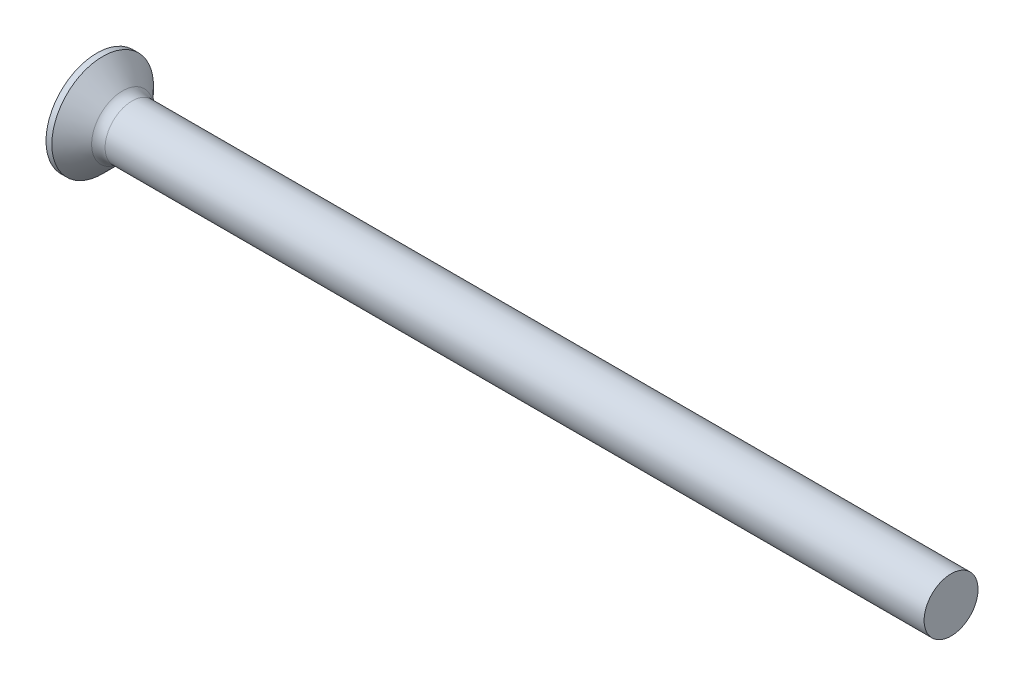
SolidWorks part; units mm, degrees
revolve "Base-Revolve" add sketch "BodySke" angle 360 about L5
sketch "BodySke" plane through (0, 0, 0) normal (0, 0, 1) x (1, 0, 0)
  line L0 (0, 0) -> (0, 5.65)
  line L1 (0, 5.65) -> (0.65, 5.65)
  line L2 (3.3, 3) -> (95, 3)
  line L3 (95, 3) -> (95, 0)
  line L4 (95, 0) -> (0, 0)
  line L5 (-6.35, 0) -> (82.55, 0) construction
  line L6 (3.3, -3) -> (95, -3) construction
  line L7 (0.65, -5.65) -> (3.3, -3) construction
  line L8 (0.65, 5.65) -> (3.3, 3)
  line L9 (0, -5.65) -> (0.65, -5.65) construction
  line L10 (4.3, 4.5875) -> (4.3, -4.9375) construction
  line L11 (57, 6.35) -> (57, -3.175) construction
  dimension "Diameter" = 6
  dimension "Length" = 95
  dimension "Head_ht" = 3.3
  dimension "Head_dia" = 11.3
  dimension "Head_ang" = 90
  dimension "D6" = 0.65
  dimension "Advance" = 1
  dimension "Thread_nom" = 38
cosmetic thread "ThreadCosmetic" [suppressed] parameters "Thread_length"=38, "Thread_minor"=4.891
ref_plane "Plane1" through (0, 0, 0) normal (0, 0, 1) x (1, 0, 0)
ref_plane "Plane2" through (0, 0, 0) normal (0, 1, 0) x (1, 0, 0)
ref_plane "Plane3" through (0, 0, 0) normal (1, 0, 0) x (0, 0, -1)
other "Configuration Table"
fillet "Fillet1" radius 1.5 1 edges at (3.3, 0, 3)
sketch "Sketch3" plane through (0, 0, 0) normal (-1, 0, 0) x (0, 0, 1)
  line L0 (-0.71, 3.3) -> (0.71, 3.3)
  line L1 (0.71, 3.3) -> (0.71, -3.3)
  line L2 (0.71, -3.3) -> (-0.71, -3.3)
  line L3 (-0.71, -3.3) -> (-0.71, 3.3)
  dimension "Cross_dia" = 6.6
  dimension "Cross_width" = 1.42
  dimension "D1" = 3.3
  dimension "D2" = 0.71
ref_plane "Plane4" through (3.45, 0, 0) normal (-1, 0, 0) x (0, 0, 1)
sketch "Sketch4" plane through (3.45, 0, 0) normal (-1, 0, 0) x (0, 0, 1)
  line L0 (-0.71, 1.5799) -> (0.71, 1.5799)
  line L3 (0.71, 1.5799) -> (0.71, -1.5799)
  line L4 (0.71, -1.5799) -> (-0.71, -1.5799)
  line L5 (-0.71, -1.5799) -> (-0.71, 1.5799)
  dimension "D2" = 3.1598
  dimension "D1" = 1.42
  dimension "D4" = 1.5799
  dimension "D3" = 0.71
loft "Recess" cut profiles "Sketch3", "Sketch4"
pattern_circular "RecPat" count 2 every 90 about axis through (0, 0, 0) along (1, 0, 0) of "Recess"
sketch "RecCorSke" plane through (0, 0, 0) normal (0, 0, 1) x (1, 0, 0)
  line L0 (-3.175, 0) -> (15.875, 0) construction
  line L2 (0, 0) -> (0, 1.5217)
  line L3 (0, 1.5217) -> (3.45, 1.2805)
  line L4 (3.45, 1.2805) -> (3.8661, 0)
  line L5 (3.8661, 0) -> (0, 0)
  dimension "Diameter" = 2.561
  dimension "Depth" = 3.45
  dimension "Draft_angle" = 4
  dimension "Bottom_angle" = 18
revolve "RecessCore" cut sketch "RecCorSke" angle 360 about L0
sketch "ThdSchSke" plane through (0, 0, 0) normal (0, 0, 1) x (1, 0, 0)
  line L0 (57, -2.4455) -> (56.6117, -3)
  line L1 (57, -2.4455) -> (57.3883, -3)
  line L2 (57.3883, -3) -> (57.3883, -3.75)
  line L3 (-3.175, 0) -> (5.1513, 0) construction
  line L5 (57.3883, -3.75) -> (56.6117, -3.75)
  line L6 (56.6117, -3.75) -> (56.6117, -3)
  line L7 (0, 5.65) -> (0, -5.65) construction
  dimension "Diameter" = 6
  dimension "Thread_minor" = 4.891
  dimension "Start" = 57
revolve "ThreadSchematic" [suppressed] cut sketch "ThdSchSke" angle 360 about L3
pattern_linear "ThdSchPat" [suppressed]
equation "\"D1@Sketch3\" = \"Cross_dia@Sketch3\" / 2"
equation "\"D2@Sketch3\" = \"Cross_width@Sketch3\" / 2"
equation "\"Depth@RecCorSke\" = \"Cross_depth@Plane4\""
equation "\"D1@Sketch4\" = \"Cross_width@Sketch3\""
equation "\"D2@Sketch4\" = \"Cross_dia@Sketch3\" - 2.0 * \"Cross_depth@Plane4\" * tan(26.5  * 0.017453292)"
equation "\"D3@Sketch4\" = \"D1@Sketch4\" / 2"
equation "\"D4@Sketch4\" = \"D2@Sketch4\" / 2"
equation "\"Thread_length@ThreadCosmetic\" = ((sgn( (\"Length@BodySke\" - \"Advance@BodySke\" * 1.0 - \"Head_ht@BodySke\" ) - \"Thread_nom@BodySke\" )-1)*( (\"Length@BodySke\" - \"Advance@BodySke\" * 1.0 - \"Head_ht@BodySke\" ) - \"Thread_nom@BodySke\" ))/-2+ \"Thread_nom@BodySke\""
equation "\"Thread_minor@ThdSchSke\" = \"Thread_minor@ThreadCosmetic\""
equation "\"Diameter@ThdSchSke\" = \"Diameter@BodySke\""
equation "\"Overcut@ThdSchSke\" = \"Diameter@BodySke\" * 1.25"
equation "\"Start@ThdSchSke\" = 0.000001 + \"Length@BodySke\" - \"Thread_length@ThreadCosmetic\"  '---Countersunk---"
equation "\"Num_threads@ThdSchPat\" = int( \"Thread_length@ThreadCosmetic\" / \"Advance@BodySke\" + 0.999 )  + 1"
equation "\"Advance@ThdSchPat\" = \"Thread_length@ThreadCosmetic\" /  (\"Num_threads@ThdSchPat\" - 1) 'relax it"
